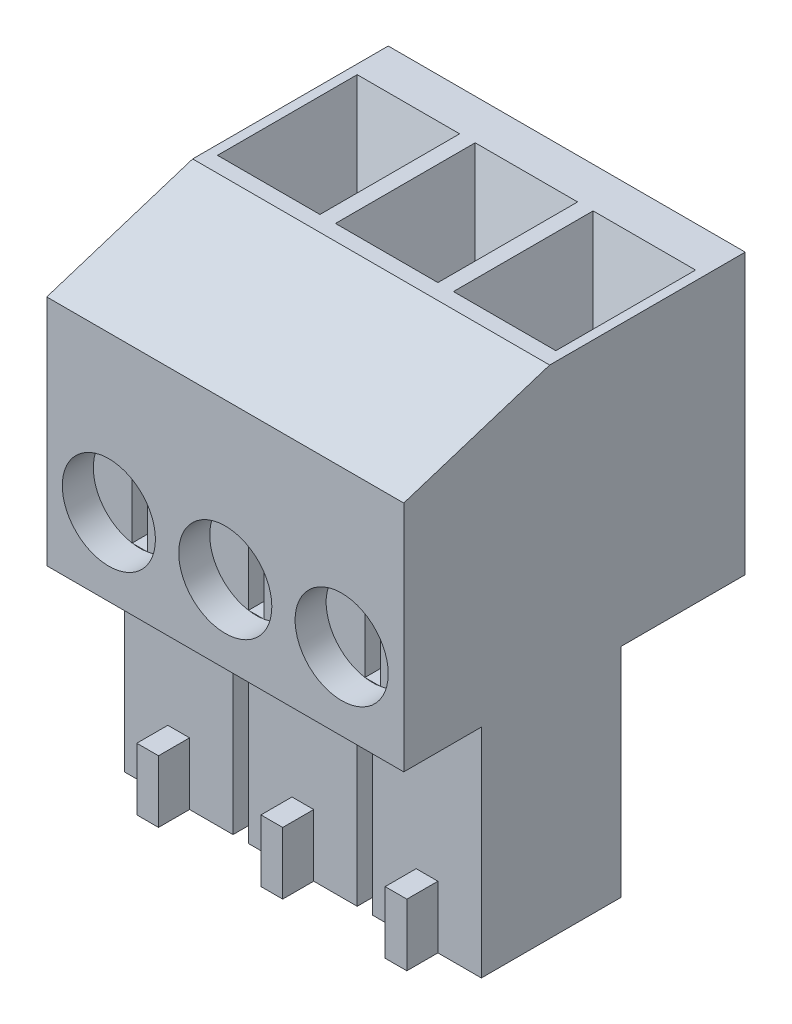
SolidWorks part; units mm, degrees
ref_plane "Front Plane" through (0, 0, 0) normal (0, 0, 1) x (1, 0, 0)
ref_plane "Top Plane" through (0, 0, 0) normal (0, 1, 0) x (1, 0, 0)
ref_plane "Right Plane" through (0, 0, 0) normal (1, 0, 0) x (0, 0, -1)
sketch "Sketch1" plane through (0, 0, 0) normal (0, 1, 0) x (1, 0, 0)
  line L1 (-5.75, 5.5) -> (5.75, 5.5)
  line L2 (-5.75, 5.5) -> (-5.75, -5.5)
  line L3 (-5.75, -5.5) -> (5.75, -5.5)
  line L4 (5.75, 5.5) -> (5.75, -5.5)
  line L5 (-5.75, 5.5) -> (5.75, -5.5) construction
  line L6 (-5.75, -5.5) -> (5.75, 5.5) construction
  point P0 (0, 0)
  dimension "D1" = 11
  dimension "D2" = 11.5
extrude "Boss-Extrude1" add sketch "Sketch1" along normal blind 9
sketch "Sketch2" plane through (0, 0, 0) normal (0, -1, 0) x (1, 0, 0)
  line L0 (-5.75, -5.5) -> (-5.75, 5.5) construction
  line L1 (-5.75, 3) -> (-2.25, 3)
  line L2 (-5.75, 3) -> (-5.75, -1.5)
  line L3 (-5.75, -1.5) -> (-2.25, -1.5)
  line L4 (-2.25, 3) -> (-2.25, -1.5)
  line L5 (-5.75, 3) -> (-2.25, -1.5) construction
  line L6 (-5.75, -1.5) -> (-2.25, 3) construction
  line L7 (2.25, 3) -> (5.75, 3)
  line L8 (2.25, 3) -> (2.25, -1.5)
  line L9 (2.25, -1.5) -> (5.75, -1.5)
  line L10 (5.75, 3) -> (5.75, -1.5)
  line L11 (2.25, 3) -> (5.75, -1.5) construction
  line L12 (2.25, -1.5) -> (5.75, 3) construction
  line L14 (5.75, 5.5) -> (5.75, -5.5) construction
  line L15 (-5.75, 5.5) -> (5.75, 5.5) construction
  line L17 (-1.75, 3) -> (1.75, 3)
  line L18 (-1.75, 3) -> (-1.75, -1.5)
  line L19 (-1.75, -1.5) -> (1.75, -1.5)
  line L20 (1.75, 3) -> (1.75, -1.5)
  line L21 (-1.75, 3) -> (1.75, -1.5) construction
  line L22 (-1.75, -1.5) -> (1.75, 3) construction
  point P0 (-4, 0.75)
  point P5 (4, 0.75)
  point P16 (0, 0.75)
  dimension "D1" = 4.5
  dimension "D2" = 3.5
  dimension "D3" = 2.5
  dimension "D4" = 0.5
extrude "Boss-Extrude2" add sketch "Sketch2" along normal blind 7
sketch "Sketch3" plane through (0, 9, 0) normal (0, 1, 0) x (1, 0, 0)
  line L0 (-5.75, 5.5) -> (-5.75, -5.5) construction
  line L1 (5.45, 4.2) -> (2.15, 4.2)
  line L2 (5.45, 4.2) -> (5.45, -0.3)
  line L3 (5.45, -0.3) -> (2.15, -0.3)
  line L4 (2.15, 4.2) -> (2.15, -0.3)
  line L5 (5.45, 4.2) -> (2.15, -0.3) construction
  line L6 (5.45, -0.3) -> (2.15, 4.2) construction
  line L7 (-2.15, 4.2) -> (-5.45, 4.2)
  line L8 (-2.15, 4.2) -> (-2.15, -0.3)
  line L9 (-2.15, -0.3) -> (-5.45, -0.3)
  line L10 (-5.45, 4.2) -> (-5.45, -0.3)
  line L11 (-2.15, 4.2) -> (-5.45, -0.3) construction
  line L12 (-2.15, -0.3) -> (-5.45, 4.2) construction
  line L13 (5.75, -5.5) -> (5.75, 5.5) construction
  line L14 (5.75, 5.5) -> (-5.75, 5.5) construction
  line L16 (-1.65, 4.2) -> (1.65, 4.2)
  line L17 (-1.65, 4.2) -> (-1.65, -0.3)
  line L18 (-1.65, -0.3) -> (1.65, -0.3)
  line L19 (1.65, 4.2) -> (1.65, -0.3)
  line L20 (-1.65, 4.2) -> (1.65, -0.3) construction
  line L21 (-1.65, -0.3) -> (1.65, 4.2) construction
  point P0 (3.8, 1.95)
  point P5 (-3.8, 1.95)
  point P16 (0, 1.95)
  dimension "D1" = 0.3
  dimension "D2" = 0.3
  dimension "D3" = 0.5
  dimension "D4" = 1.3
  dimension "D5" = 4.5
  dimension "D6" = 0.5
extrude "Cut-Extrude1" cut sketch "Sketch3" against normal blind 3 draft 15
sketch "Sketch4" plane through (0, 6, 0) normal (0, 1, 0) x (1, 0, 0)
  line L1 (-2.9538, 3.3962) -> (-4.6462, 3.3962)
  line L2 (-2.9538, 3.3962) -> (-2.9538, 0.5038)
  line L3 (-2.9538, 0.5038) -> (-4.6462, 0.5038)
  line L4 (-4.6462, 3.3962) -> (-4.6462, 0.5038)
  line L5 (4.6462, 3.3962) -> (2.9538, 3.3962)
  line L6 (4.6462, 3.3962) -> (4.6462, 0.5038)
  line L7 (4.6462, 0.5038) -> (2.9538, 0.5038)
  line L8 (2.9538, 3.3962) -> (2.9538, 0.5038)
  line L9 (0.8462, 3.3962) -> (-0.8462, 3.3962)
  line L10 (0.8462, 3.3962) -> (0.8462, 0.5038)
  line L11 (0.8462, 0.5038) -> (-0.8462, 0.5038)
  line L12 (-0.8462, 3.3962) -> (-0.8462, 0.5038)
extrude "Cut-Extrude2" cut sketch "Sketch4" against normal blind 3
sketch "Sketch5" plane through (-5.75, 0, 0) normal (-1, 0, 0) x (0, 0, 1)
  line L0 (5.5, 9) -> (0.8, 9)
  line L1 (-5.5, 9) -> (5.5, 9) construction
  line L2 (0.8, 9) -> (5.5, 7.5)
  line L3 (5.5, 9) -> (5.5, 0) construction
  line L4 (5.5, 7.5) -> (5.5, 9)
  dimension "D1" = 1.5
  dimension "D2" = 0.5
extrude "Cut-Extrude3" cut sketch "Sketch5" against normal blind 17
sketch "Sketch6" plane through (0, 0, 5.5) normal (0, 0, 1) x (1, 0, 0)
  line L0 (-5.75, 7.5) -> (-5.75, 0) construction
  line L1 (5.75, 7.5) -> (5.75, 0) construction
  circle A0 centre (-3.75, 2.4872) radius 1.5
  circle A1 centre (0, 2.4872) radius 1.5
  circle A2 centre (3.75, 2.4872) radius 1.5
  dimension "D2" = 3
  dimension "D3" = 3.75
  dimension "D4" = 2
  dimension "D5" = 2
extrude "Cut-Extrude4" cut sketch "Sketch6" against normal blind 1
sketch "Sketch7" plane through (0, 0, 4.5) normal (0, 0, 1) x (1, 0, 0)
  line L1 (-4, 3.9662) -> (-3.5, 3.9662)
  line L2 (-4, 3.9662) -> (-4, 1.0082)
  line L3 (-4, 1.0082) -> (-3.5, 1.0082)
  line L4 (-3.5, 3.9662) -> (-3.5, 1.0082)
  line L5 (-4, 3.9662) -> (-3.5, 1.0082) construction
  line L6 (-4, 1.0082) -> (-3.5, 3.9662) construction
  line L7 (0.25, 3.9662) -> (-0.25, 3.9662)
  line L8 (0.25, 3.9662) -> (0.25, 1.0082)
  line L9 (0.25, 1.0082) -> (-0.25, 1.0082)
  line L10 (-0.25, 3.9662) -> (-0.25, 1.0082)
  line L11 (0.25, 3.9662) -> (-0.25, 1.0082) construction
  line L12 (0.25, 1.0082) -> (-0.25, 3.9662) construction
  line L13 (3.5, 3.9662) -> (4, 3.9662)
  line L14 (3.5, 3.9662) -> (3.5, 1.0082)
  line L15 (3.5, 1.0082) -> (4, 1.0082)
  line L16 (4, 3.9662) -> (4, 1.0082)
  line L17 (3.5, 3.9662) -> (4, 1.0082) construction
  line L18 (3.5, 1.0082) -> (4, 3.9662) construction
  circle A0 centre (-3.75, 2.4872) radius 1.5 construction
  circle A1 centre (0, 2.4872) radius 1.5 construction
  circle A2 centre (3.75, 2.4872) radius 1.5 construction
  point P0 (-3.75, 2.4872)
  point P8 (0, 2.4872)
  point P16 (3.75, 2.4872)
  dimension "D1" = 0.5
extrude "Cut-Extrude5" cut sketch "Sketch7" against normal blind 0.5
sketch "Sketch8" plane through (0, 0, 3) normal (0, 0, 1) x (1, 0, 0)
  line L1 (4.35, -5) -> (3.65, -5)
  line L2 (4.35, -5) -> (4.35, -7)
  line L3 (4.35, -7) -> (3.65, -7)
  line L4 (3.65, -5) -> (3.65, -7)
  line L5 (4.35, -5) -> (3.65, -7) construction
  line L6 (4.35, -7) -> (3.65, -5) construction
  line L7 (-3.65, -5) -> (-4.35, -5)
  line L8 (-3.65, -5) -> (-3.65, -7)
  line L9 (-3.65, -7) -> (-4.35, -7)
  line L10 (-4.35, -5) -> (-4.35, -7)
  line L11 (-3.65, -5) -> (-4.35, -7) construction
  line L12 (-3.65, -7) -> (-4.35, -5) construction
  line L13 (-2.25, -7) -> (-5.75, -7) construction
  line L14 (5.75, -7) -> (2.25, -7) construction
  line L15 (0.35, -5) -> (-0.35, -5)
  line L16 (0.35, -5) -> (0.35, -7)
  line L17 (0.35, -7) -> (-0.35, -7)
  line L18 (-0.35, -5) -> (-0.35, -7)
  line L19 (0.35, -5) -> (-0.35, -7) construction
  line L20 (0.35, -7) -> (-0.35, -5) construction
  line L21 (1.75, -7) -> (-1.75, -7) construction
  point P0 (4, -6)
  point P5 (-4, -6)
  point P12 (-4, -7)
  point P13 (4, -7)
  point P16 (0, -6)
  point P23 (0, -7)
  dimension "D1" = 0.7
  dimension "D2" = 0.7
  dimension "D3" = 2
  dimension "D4" = 2
  dimension "D5" = 0.7
  dimension "D6" = 2
extrude "Boss-Extrude3" add sketch "Sketch8" along normal blind 1
